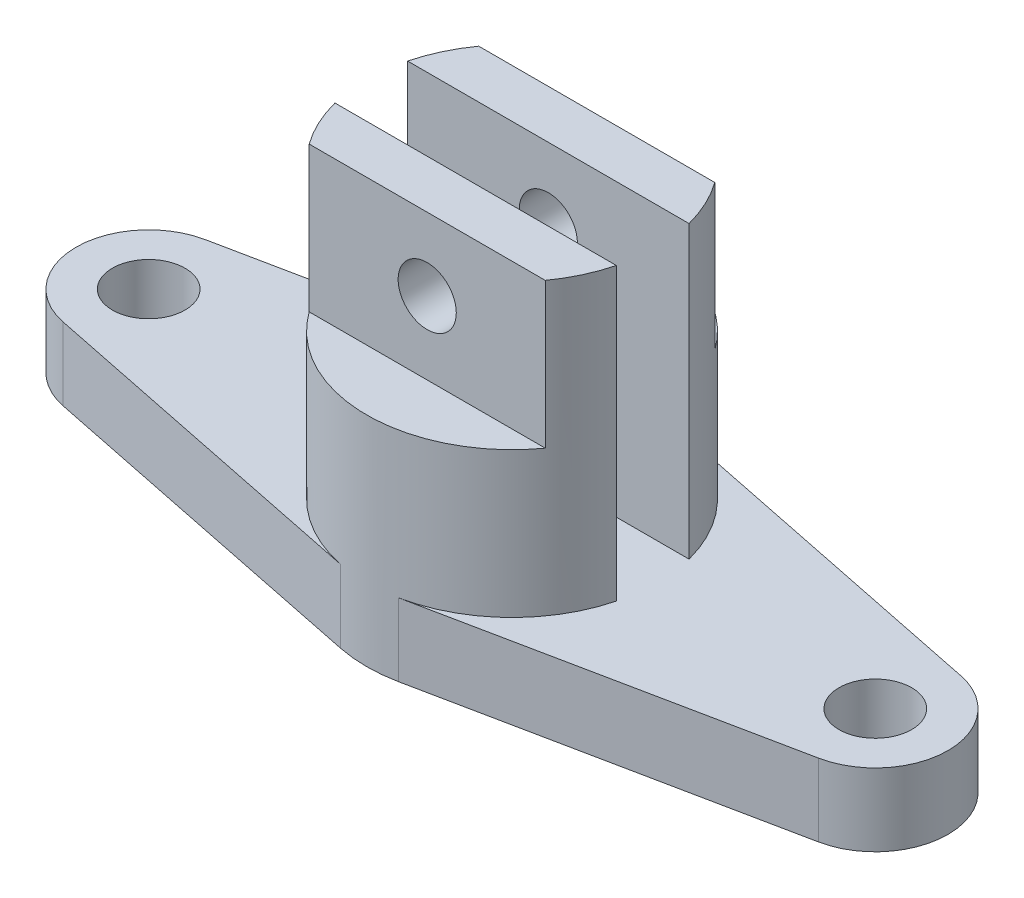
SolidWorks part; units mm, degrees
ref_plane "Front Plane" through (0, 0, 0) normal (0, 0, 1) x (1, 0, 0)
ref_plane "Top Plane" through (0, 0, 0) normal (0, 1, 0) x (1, 0, 0)
ref_plane "Right Plane" through (0, 0, 0) normal (1, 0, 0) x (0, 0, -1)
sketch "Sketch1" plane through (0, 0, 0) normal (0, 1, 0) x (1, 0, 0)
  line L0 (-75, 0) -> (46.4582, 0) construction
  line L1 (0, 51.8558) -> (0, -49.7518) construction
  line L2 (-6, 29.3939) -> (-78, 14.6969)
  line L3 (-6, -29.3939) -> (-78, -14.6969)
  line L4 (6, -29.3939) -> (78, -14.6969)
  line L5 (6, 29.3939) -> (78, 14.6969)
  circle A0 centre (-75, 0) radius 7.5
  arc A1 (-78, 14.6969) -> (-78, -14.6969) centre (-75, 0) ccw
  arc A2 (-6, -29.3939) -> (6, -29.3939) centre (0, 0) ccw
  arc A3 (78, 14.6969) -> (78, -14.6969) centre (75, 0) cw
  circle A4 centre (75, 0) radius 7.5
  arc A5 (6, 29.3939) -> (-6, 29.3939) centre (0, 0) ccw
  dimension "D1" = 30
  dimension "D2" = 15
  dimension "D3" = 60
  dimension "D4" = 75
extrude "Boss-Extrude1" add sketch "Sketch1" along normal blind 15
sketch "Sketch2" plane through (0, 15, 0) normal (0, 1, 0) x (1, 0, 0)
  line L0 (-100.3166, 0) -> (106.9858, 0) construction
  line L1 (0, 40.0155) -> (0, -46.4068) construction
  line L2 (-29.0474, -7.5) -> (29.0474, -7.5)
  arc A0 (-29.0474, -7.5) -> (29.0474, -7.5) centre (0, 0) ccw
  arc A1 (6, 29.3939) -> (-6, 29.3939) centre (0, 0) ccw construction
  dimension "D1" = 7.5
extrude "Boss-Extrude2" add sketch "Sketch2" along normal blind 60 contours A0 L2
sketch "Sketch4" plane through (0, 75, 0) normal (0, 1, 0) x (1, 0, 0)
  line L0 (-93.9252, 0) -> (97.8156, 0) construction
  line L1 (29.0474, -7.5) -> (-29.0474, -7.5)
  line L3 (0, 50.0193) -> (0, -57.2444) construction
  line L4 (-24.367, -17.5) -> (24.367, -17.5)
  arc A1 (-29.0474, -7.5) -> (29.0474, -7.5) centre (0, 0) ccw
  arc A2 (-24.367, -17.5) -> (24.367, -17.5) centre (0, 0) ccw
  dimension "D2" = 17.5
  dimension "D1" = 0
extrude "Cut-Extrude2" cut sketch "Sketch4" against normal blind 30 contours L4 A2
mirror "Mirror2" about plane through (0, 0, 0) normal (0, 0, 1) of "Boss-Extrude2"
mirror "Mirror3" about plane through (0, 0, 0) normal (0, 0, 1) of "Cut-Extrude2"
sketch "Sketch5" plane through (0, 0, 17.5) normal (0, 0, 1) x (1, 0, 0)
  line L1 (6, 0) -> (78, 0) construction
  circle A0 centre (0, 60) radius 6
  point P2 (0, 0)
  point P5 (1.6673, 59.7308)
  dimension "D1" = 12
  dimension "D2" = 90
  dimension "D3" = 60
extrude "Cut-Extrude3" cut sketch "Sketch5" against normal through all and the other way through all
